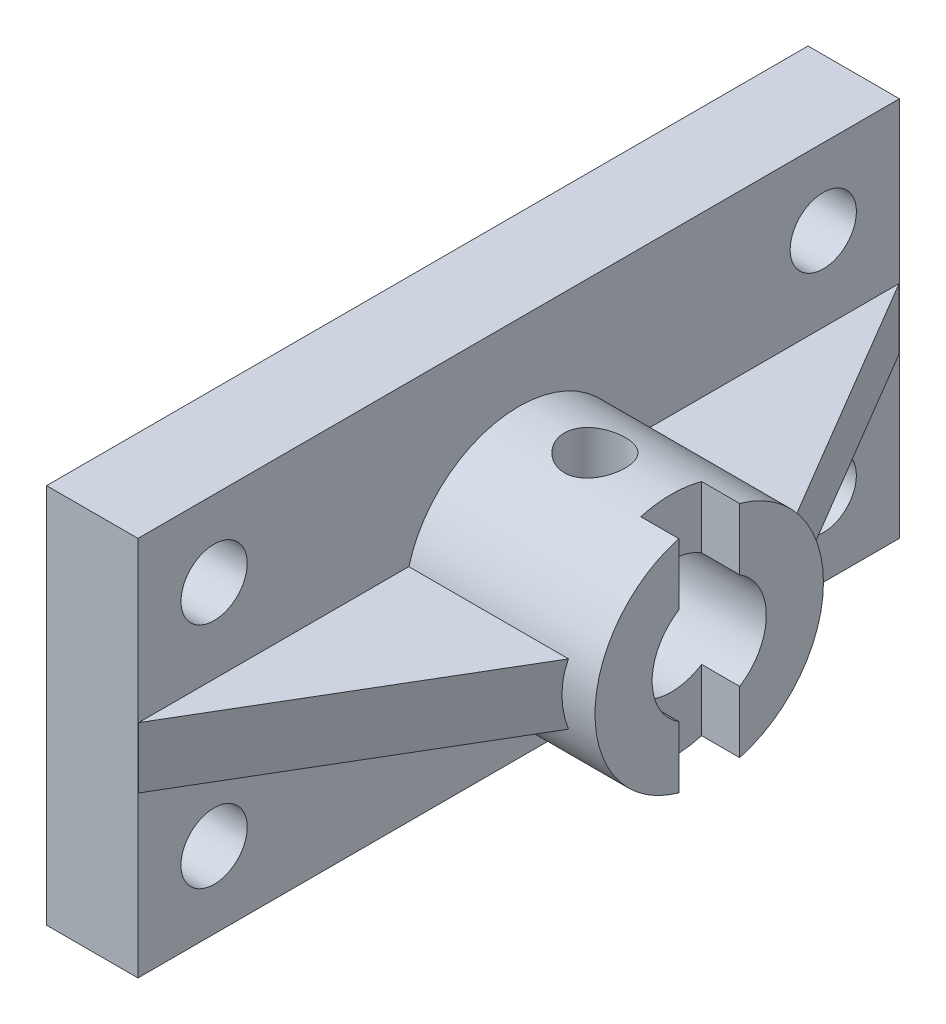
SolidWorks part; units mm, degrees
ref_plane "前视基准面" through (0, 0, 0) normal (0, 0, 1) x (1, 0, 0)
ref_plane "上视基准面" through (0, 0, 0) normal (0, 1, 0) x (1, 0, 0)
ref_plane "右视基准面" through (0, 0, 0) normal (1, 0, 0) x (0, 0, -1)
other "Configuration Table"
sketch "草图1" plane through (0, 0, 0) normal (1, 0, 0) x (0, 0, -1)
  line L0 (0, 0) -> (100, 0)
  line L1 (100, 0) -> (100, 50)
  line L2 (100, 50) -> (0, 50)
  line L3 (0, 50) -> (0, 0)
  dimension "D1" = 100
  dimension "D2" = 50
extrude "凸台-拉伸1" add sketch "草图1" along normal blind 12
sketch "草图2" plane through (12, 0, 0) normal (1, 0, 0) x (0, 0, -1)
  line L0 (0, 25) -> (99.6027, 25) construction
  line L2 (50, 25) -> (50, 54.1995) construction
  line L3 (100, 0) -> (100, 50) construction
  line L4 (100, 50) -> (0, 50) construction
  circle A0 centre (10, 10) radius 4
  circle A1 centre (90, 10) radius 4
  circle A2 centre (90, 40) radius 4
  circle A3 centre (10, 40) radius 4
  circle A4 centre (50.0252, 25) radius 15
  circle A5 centre (50.0252, 25) radius 7.5
  point P16 (50.0252, 21.8781)
  dimension "D2" = 8
  dimension "D5" = 30
  dimension "D1" = 50
  dimension "D3" = 80
  dimension "D4" = 30
  dimension "D7" = 25
  dimension "D6" = 7.5
extrude "凸台-拉伸3" add sketch "草图2" along normal blind 25 contours A4 | A5
ref_plane "基准面1" through (0, 25, 0) normal (0, 1, 0) x (1, 0, 0)
sketch "草图6" plane through (0, 25, 0) normal (0, 1, 0) x (1, 0, 0)
  line L4 (12, 50.0252) -> (46.7865, 50.0252) construction
  line L13 (11.6079, 61.8998) -> (11.9747, 100)
  line L14 (11.6079, 61.8998) -> (34.4981, 61.8998)
  line L15 (34.4981, 61.8998) -> (11.9747, 100)
  line L16 (11.6079, 38.1507) -> (34.4981, 38.1507)
  line L17 (34.4981, 38.1507) -> (11.9747, 0.0505)
  line L18 (11.6079, 38.1507) -> (11.9747, 0.0505)
  line L19 (12, 100) -> (0, 100) construction
  point P4 (11.4822, 100)
  point P8 (12.0429, 100.3103)
  point P9 (0, 0)
  point P10 (0, 0)
  point P12 (12.0429, 99.989)
  point P15 (11.8216, 100)
  point P18 (11.9747, 100)
extrude "凸台-拉伸20" add sketch "草图6" along normal mid plane 8
sketch "草图7" plane through (12, 0, 0) normal (1, 0, 0) x (0, 0, -1)
  circle A1 centre (50.0252, 25) radius 7.5
  circle A2 centre (50.0252, 25) radius 7.5
  dimension "D1" = 0
extrude "切除-拉伸2" cut sketch "草图7" against normal through all contours A2
sketch "草图8" plane through (0, 25, 0) normal (0, 1, 0) x (1, 0, 0)
  line L0 (0, 50.0252) -> (39.0346, 50.0252) construction
  line L2 (37, 54.0252) -> (32, 54.0252)
  line L3 (37, 35.0252) -> (37, 65.0252) construction
  line L4 (32, 54.0252) -> (32, 46.0252)
  line L5 (37, 54.0252) -> (37, 50.0252)
  line L6 (37, 46.0252) -> (37, 50.0252)
  line L7 (37, 46.0252) -> (32, 46.0252)
  point P8 (0, 0)
  point P9 (32, 54.0252)
  point P11 (32, 50.0252)
  point P12 (32, 54.0252)
  point P13 (0, 0)
  point P14 (32, 50.0252)
  point P15 (32, 50.0252)
  dimension "D1" = 4
  dimension "D2" = 5
extrude "切除-拉伸4" cut sketch "草图8" against normal through all and the other way through all contours L5 L6 L7 L4 L2
sketch "草图9" plane through (0, 25, 0) normal (0, 1, 0) x (1, 0, 0)
  line L0 (35.9079, 50.0252) -> (15.9079, 50) construction
  line L3 (12, 35.5684) -> (12, 64.4821) construction
  circle A0 centre (22, 50.0077) radius 4
  point P3 (0, 0)
  point P7 (0, 0)
  dimension "D1" = 8
  dimension "D2" = 10
extrude "切除-拉伸5" cut sketch "草图9" against normal through all and the other way through all
sketch "草图10" plane through (12, 0, 0) normal (1, 0, 0) x (0, 0, -1)
  line L0 (36.5892, 25) -> (-36.5892, 25) construction
  line L1 (0, 50) -> (0, 0) construction
  line L2 (50, 50) -> (50, 0) construction
  circle A0 centre (10, 40) radius 4.3491
  circle A1 centre (10, 10) radius 4.3491
  circle A2 centre (90, 10) radius 4.3491
  circle A3 centre (90, 40) radius 4.3491
  dimension "D1" = 15
  dimension "D2" = 10
extrude "切除-拉伸6" cut sketch "草图10" against normal through all
